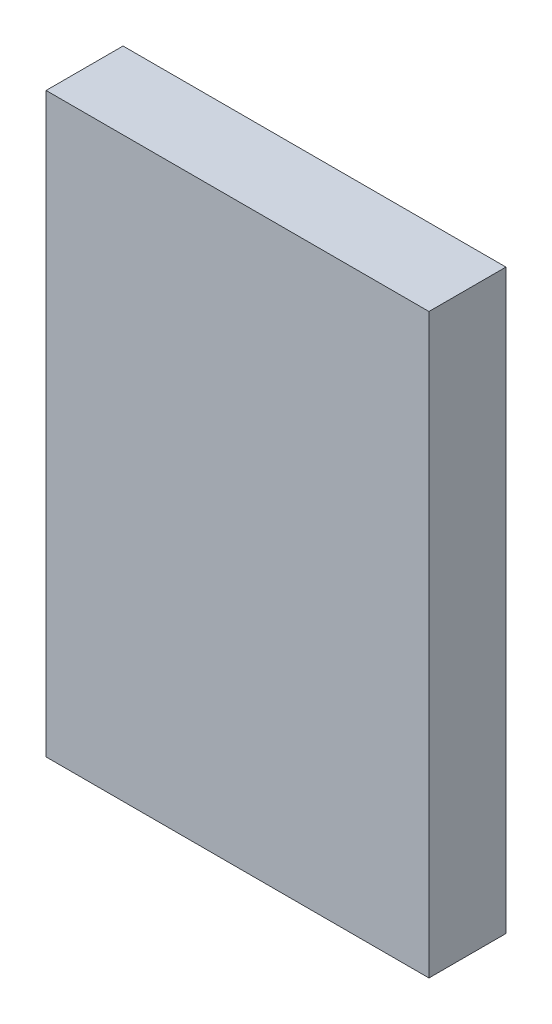
SolidWorks part; units mm, degrees
ref_plane "Front Plane" through (0, 0, 0) normal (0, 0, 1) x (1, 0, 0)
ref_plane "Top Plane" through (0, 0, 0) normal (0, 1, 0) x (1, 0, 0)
ref_plane "Right Plane" through (0, 0, 0) normal (1, 0, 0) x (0, 0, -1)
sketch "Sketch1" plane through (0, 0, 0) normal (0, 0, 1) x (1, 0, 0)
  line L1 (4.975, -7.5) -> (-4.975, -7.5)
  line L2 (4.975, -7.5) -> (4.975, 7.5)
  line L3 (4.975, 7.5) -> (-4.975, 7.5)
  line L4 (-4.975, -7.5) -> (-4.975, 7.5)
  line L5 (4.975, -7.5) -> (-4.975, 7.5) construction
  line L6 (4.975, 7.5) -> (-4.975, -7.5) construction
  point P0 (0, 0)
  dimension "D1" = 15
  dimension "D2" = 9.95
extrude "Boss-Extrude1" add sketch "Sketch1" along normal blind 2
